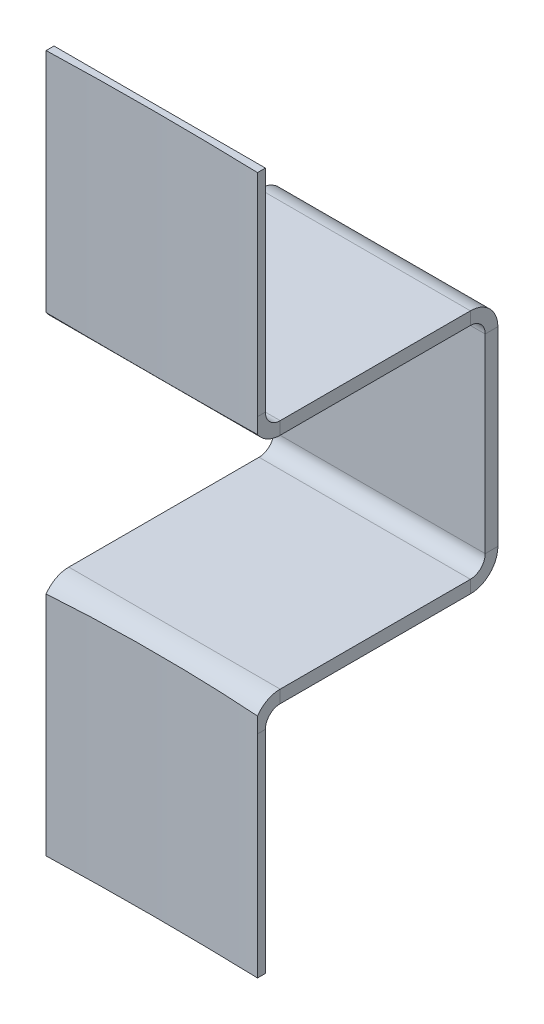
SolidWorks part; units mm, degrees
ref_plane "Front Plane" through (0, 0, 0) normal (0, 0, 1) x (1, 0, 0)
ref_plane "Top Plane" through (0, 0, 0) normal (0, 1, 0) x (1, 0, 0)
ref_plane "Right Plane" through (0, 0, 0) normal (1, 0, 0) x (0, 0, -1)
sketch "Sketch2" plane through (0, 0, 0) normal (1, 0, 0) x (0, 0, -1)
  line L0 (0, 0) -> (0, -10)
  line L1 (1, -11) -> (10, -11)
  line L2 (11, -12) -> (11, -21)
  line L3 (10, -22) -> (1, -22)
  line L4 (0, -23) -> (0, -33)
  arc A0 (11, -12) -> (10, -11) centre (10, -12) ccw
  arc A1 (10, -22) -> (11, -21) centre (10, -21) ccw
  arc A2 (0, -23) -> (1, -22) centre (1, -23) cw
  arc A3 (0, -10) -> (1, -11) centre (1, -10) ccw
  point P9 (11, -11)
  point P12 (11, -22)
  point P15 (0, -22)
  point P18 (0, -11)
  dimension "D5" = 1
  dimension "D6" = 1
  dimension "D7" = 1
  dimension "D8" = 1
  dimension "D1" = 11
  dimension "D2" = 11
  dimension "D3" = 11
  dimension "D4" = 11
sketch "Sketch3" plane through (0, 0, 0) normal (0, 1, 0) x (1, 0, 0)
  line L1 (-5, 0.3) -> (5, 0.3)
  line L2 (-5, 0.3) -> (-5, -0.3)
  line L3 (-5, -0.3) -> (5, -0.3)
  line L4 (5, 0.3) -> (5, -0.3)
  line L5 (-5, 0.3) -> (5, -0.3) construction
  line L6 (-5, -0.3) -> (5, 0.3) construction
  point P0 (0, 0)
  dimension "D1" = 10
  dimension "D2" = 0.6
sweep "Sweep1" add profiles "Sketch3" path "Sketch2"
sketch "Sketch5" plane through (0, 0, 0) normal (0, 1, 0) x (1, 0, 0)
  circle A0 centre (0, -169.599) radius 169.6
  point P2 (-8.1283, -183.1835)
  point P3 (0, -169.4925)
  point P4 (0, 0)
  point P6 (0, 0)
  dimension "D1" = 339.2
  dimension "D2" = 169.599
extrude "Cut-Extrude1" cut sketch "Sketch5" against normal through all
equation "\"D1@Sketch2\"=11.000000mm"
equation "\"D6@Sketch2\"=1.000000mm"
equation "\"D5@Sketch2\"=1.000000mm"
equation "\"D8@Sketch2\"=1.000000mm"
equation "\"D3@Sketch2\"=11.000000mm"
equation "\"D2@Sketch2\"=11.000000mm"
equation "\"D4@Sketch2\"=11.000000mm"
equation "\"D2@Sketch3\"=0.600000mm"
equation "\"D1@Sketch3\"=10.000000mm"
equation "\"Height\"= 173.1cm"
equation "\"Waist\" = 33.92cm"
equation "\"D1@Sketch5\"=\"Waist\""
equation "\"D2@Sketch5\"=(\"Waist\"/2)-0.001"
